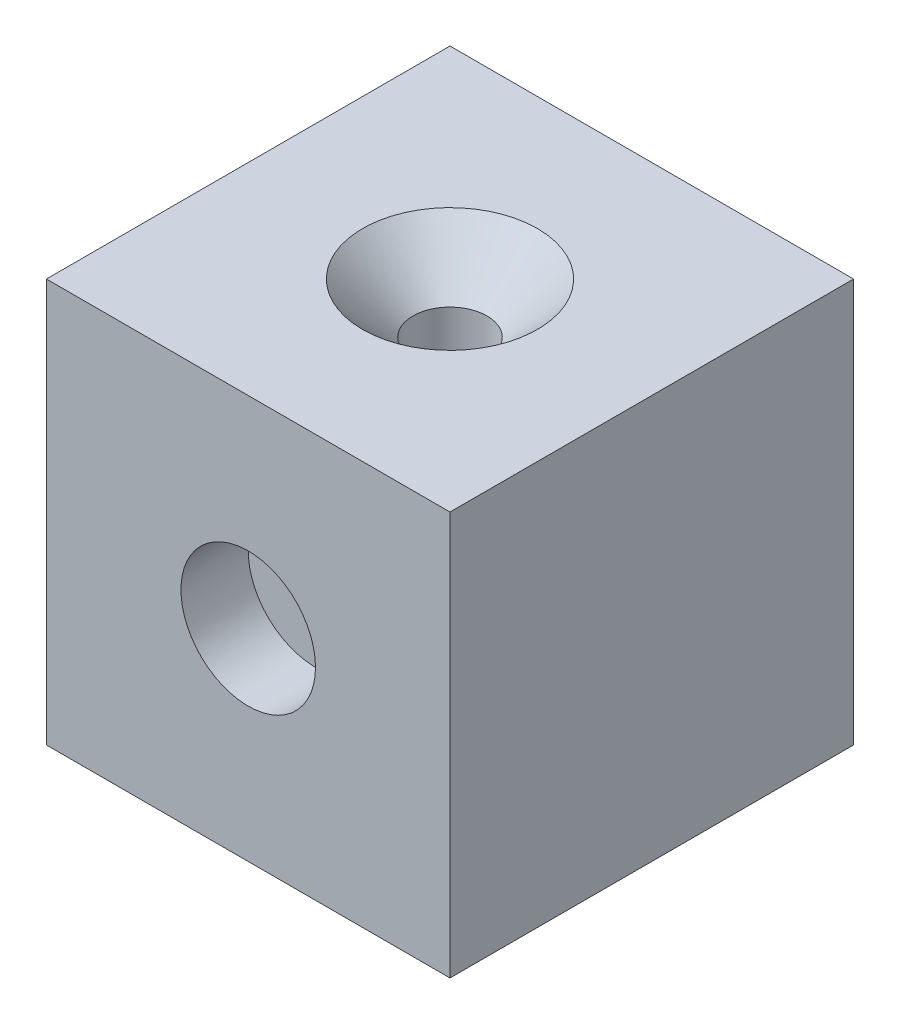
SolidWorks part; units mm, degrees
ref_plane "Front Plane" through (0, 0, 0) normal (0, 0, 1) x (1, 0, 0)
ref_plane "Top Plane" through (0, 0, 0) normal (0, 1, 0) x (1, 0, 0)
ref_plane "Right Plane" through (0, 0, 0) normal (1, 0, 0) x (0, 0, -1)
sketch "Sketch1" plane through (0, 0, 0) normal (0, 1, 0) x (1, 0, 0)
  line L0 (-76.2, 76.2) -> (76.2, -76.2) construction
  line L1 (-76.2, 76.2) -> (76.2, 76.2)
  line L2 (-76.2, 76.2) -> (-76.2, -76.2)
  line L3 (-76.2, -76.2) -> (76.2, -76.2)
  line L4 (76.2, 76.2) -> (76.2, -76.2)
  dimension "D1" = 152.4
extrude "Boss-Extrude1" add sketch "Sketch1" along normal mid plane 152.4
sketch "Sketch2" plane through (0, 0, 0) normal (0, 0, 1) x (1, 0, 0)
  line L0 (0, 0) -> (0, 12.7) construction
  line L1 (0, 12.7) -> (13.97, 12.7)
  line L2 (13.97, 12.7) -> (13.97, 57.15)
  line L3 (13.97, 57.15) -> (33.02, 76.2)
  line L4 (-76.2, 76.2) -> (76.2, 76.2) construction
  line L5 (33.02, 76.2) -> (0, 76.2)
  line L6 (0, 76.2) -> (0, 12.7)
  dimension "D1" = 45
  dimension "D2" = 13.97
  dimension "D3" = 63.5
  dimension "D4" = 19.05
revolve "Cut-Revolve1" cut sketch "Sketch2" angle 360 about L0
sketch "Sketch4" plane through (0, 0, 76.2) normal (0, 0, 1) x (1, 0, 0)
  circle A0 centre (0, 0) radius 25.4
  dimension "D1" = 50.8
extrude "Cut-Extrude2" cut sketch "Sketch4" against normal blind 25.4
sketch "Sketch5" plane through (0, 0, -76.2) normal (0, 0, -1) x (-1, 0, 0)
  circle A0 centre (0, 0) radius 25.4
  dimension "D1" = 50.8
extrude "Boss-Extrude2" add sketch "Sketch5" along normal blind 25.4
sketch "Sketch6" plane through (-76.2, 0, 0) normal (-1, 0, 0) x (0, 0, 1)
  line L0 (-63.5, 63.5) -> (63.5, -63.5) construction
  line L1 (-63.5, 63.5) -> (63.5, 63.5)
  line L2 (-63.5, 63.5) -> (-63.5, -63.5)
  line L3 (-63.5, -63.5) -> (63.5, -63.5)
  line L4 (63.5, 63.5) -> (63.5, -63.5)
  line L5 (-76.2, 76.2) -> (76.2, 76.2) construction
  dimension "D1" = 12.7
extrude "Cut-Extrude3" cut sketch "Sketch6" against normal blind 12.7
